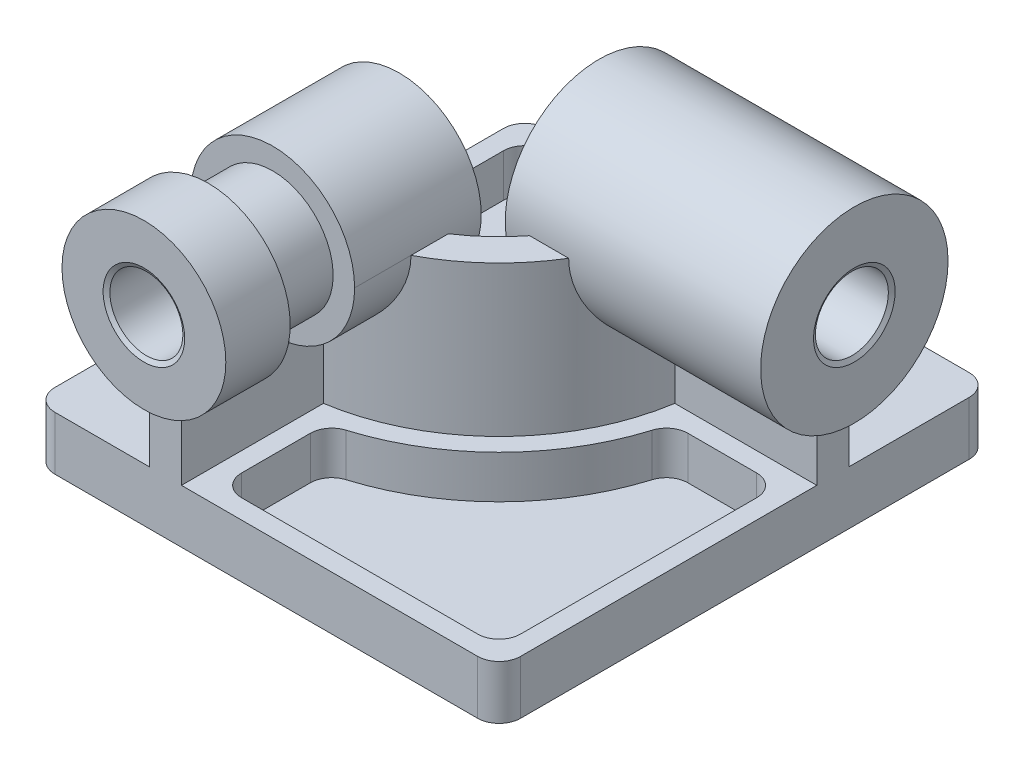
SolidWorks part; units mm, degrees
material "Alloy Steel"
ref_plane "Front Plane" through (0, 0, 0) normal (0, 0, 1) x (1, 0, 0)
ref_plane "Top Plane" through (0, 0, 0) normal (0, 1, 0) x (1, 0, 0)
ref_plane "Right Plane" through (0, 0, 0) normal (1, 0, 0) x (0, 0, -1)
sketch "Sketch1" plane through (0, 0, 0) normal (0, 1, 0) x (1, 0, 0)
  line L0 (0, 0) -> (0, -163) construction
  line L1 (-44, 66) -> (153, 66)
  line L2 (-54, 56) -> (-54, -153)
  line L3 (-44, -163) -> (153, -163)
  line L4 (163, 56) -> (163, -153)
  line L6 (21.1729, -100.3509) -> (22.0551, -100.3509) construction
  line L8 (0, 0) -> (163, 0) construction
  arc A0 (-44, 66) -> (-54, 56) centre (-44, 56) ccw
  arc A1 (-54, -153) -> (-44, -163) centre (-44, -153) ccw
  arc A2 (153, -163) -> (163, -153) centre (153, -153) ccw
  arc A3 (153, 66) -> (163, 56) centre (153, 56) cw
  dimension "D5" = 10
  dimension "D1" = 163
  dimension "D2" = 163
  dimension "D3" = 229
  dimension "D4" = 217
extrude "Boss-Extrude1" add sketch "Sketch1" along normal blind 25
sketch "Sketch2" plane through (0, 25, 0) normal (0, 1, 0) x (1, 0, 0)
  line L0 (0, -83) -> (0, -163)
  line L1 (-44, -163) -> (153, -163) construction
  line L2 (83, 0) -> (163, 0)
  line L3 (163, -153) -> (163, 56) construction
  line L4 (15, -96.8452) -> (15, -163)
  line L5 (96.8452, -15) -> (163, -15)
  line L6 (163, 0) -> (163, -15)
  line L7 (0, -163) -> (15, -163)
  arc A0 (0, -83) -> (83, 0) centre (0, 0) ccw
  arc A1 (15, -96.8452) -> (96.8452, -15) centre (0, 0) ccw
  dimension "D1" = 80
  dimension "D2" = 15
extrude "Boss-Extrude2" add sketch "Sketch2" along normal blind 95 from surface at -25 starting at face at (54.5, 0, 48.5)
sketch "Sketch3" plane through (0, 25, 0) normal (0, 1, 0) x (1, 0, 0)
  line L0 (15, -163) -> (153, -163) construction
  line L1 (118, -103) -> (163, -103)
  line L2 (103, -118) -> (103, -163)
  line L3 (103, -163) -> (153, -163)
  line L4 (163, -103) -> (163, -153)
  line L5 (163, -153) -> (163, -15) construction
  arc A0 (153, -163) -> (163, -153) centre (153, -153) ccw construction
  arc A1 (153, -163) -> (163, -153) centre (153, -153) ccw
  arc A2 (118, -103) -> (103, -118) centre (118, -118) ccw
  dimension "D3" = 15
  dimension "D1" = 60
  dimension "D2" = 60
extrude "Boss-Extrude3" [suppressed] add sketch "Sketch3" along normal blind 10
hole_wizard "CBORE for M8 Hex Head Bolt1" [suppressed] positions "Sketch5" profile "Sketch4" counterbore size "M8" standard "ANSI Metric"
sketch "Sketch5" [suppressed] plane through (0, 35, 0) normal (0, 1, 0) x (1, 0, 0)
  line L0 (105, -165) -> (155, -165) construction
  line L2 (165, -155) -> (165, -105) construction
  point P0 (135, -135)
  dimension "D1" = 30
  dimension "D2" = 30
sketch "Sketch4" plane through (135, 35, 135) normal (1, 0, 0) x (0, 0, 1)
  line L0 (0, 0) -> (0, 35)
  line L1 (0, 35) -> (7.5, 35)
  line L3 (7.5, 35) -> (7.5, 10)
  line L4 (7.5, 10) -> (15, 10)
  line L5 (15, 10) -> (15, 0)
  line L7 (15, 0) -> (0, 0)
  line L11 (0, -6.35) -> (0, 107.95) construction
  dimension "Thru Hole Dia." = 15
  dimension "Thru Hole Depth" = 35
  dimension "C'Bore Dia." = 30
  dimension "C'Bore Depth" = 10
sketch "Sketch6" plane through (0, 25, 0) normal (0, 1, 0) x (1, 0, 0)
  line L10 (154, -24) -> (104.2737, -24)
  line L11 (154, -24) -> (104.2737, -24)
  line L12 (24, -154) -> (153, -154)
  line L13 (24, -104.2737) -> (24, -154)
  line L14 (24, -104.2737) -> (24, -154)
  line L15 (154, -153) -> (154, -24)
  line L18 (20, -154) -> (86, -154)
  line L21 (154, -145) -> (154, -38)
  arc A2 (114.0395, -24) -> (104.4563, -31.1429) centre (114.0395, -34) ccw
  arc A3 (154, -38) -> (149.2411, -29.4835) centre (144, -38) ccw
  arc A4 (153, -154) -> (154, -153) centre (153, -153) ccw
  arc A5 (24, -104.2737) -> (104.2737, -24) centre (0, 0) ccw
  arc A6 (153, -154) -> (154, -153) centre (153, -153) ccw
  arc A7 (24, -104.2737) -> (104.2737, -24) centre (0, 0) ccw
  arc A8 (146.2185, -154.7508) -> (154, -145) centre (144, -145) ccw
  arc A9 (86, -154) -> (95.7508, -146.2185) centre (86, -144) ccw
  arc A10 (20, -154) -> (11.4835, -149.2411) centre (20, -144) cw
  arc A11 (31.1429, -104.4563) -> (24, -114.0395) centre (34, -114.0395) ccw
  dimension "D2" = 10
  dimension "D1" = 9
extrude "Cut-Extrude1" [suppressed] cut sketch "Sketch6" against normal offset from surface (20 mm away) 5
sketch "Sketch7" plane through (0, 0, 163) normal (0, 0, 1) x (1, 0, 0)
  line L0 (0, 95) -> (15, 95) construction
  circle A0 centre (7.5, 95) radius 38.1667
  dimension "D1" = 76.3333
extrude "Boss-Extrude4" add sketch "Sketch7" against normal blind 119 from offset 10
sketch "Sketch8" plane through (163, 0, 0) normal (1, 0, 0) x (0, 0, -1)
  line L0 (-15, 95) -> (0, 95) construction
  circle A0 centre (-7.5, 95) radius 43.6667
  dimension "D1" = 87.3333
extrude "Boss-Extrude5" add sketch "Sketch8" against normal blind 119 from offset 10
sketch "Sketch9" plane through (0, 0, 173) normal (0, 0, 1) x (1, 0, 0)
  circle A0 centre (7.5, 95) radius 17
  dimension "D1" = 34
extrude "Cut-Extrude2" cut sketch "Sketch9" against normal up to next
sketch "Sketch10" plane through (173, 0, 0) normal (1, 0, 0) x (0, 0, -1)
  circle A0 centre (-7.5, 95) radius 17
  dimension "D1" = 34
extrude "Cut-Extrude3" cut sketch "Sketch10" against normal up to next
chamfer "Chamfer1" distance 2 angle 30 4 edges at (54, 95, -9.5) (24.5, 95, 54) (173, 95, -9.5) (24.5, 95, 173)
sketch "Sketch11" plane through (0, 0, 173) normal (0, 0, 1) x (1, 0, 0)
  line L0 (0, 57.5775) -> (0, 67.8502)
  line L2 (15, 67.8502) -> (15, 57.5775)
  arc A0 (15, 67.8502) -> (0, 67.8502) centre (7.5, 95) ccw
  circle A1 centre (7.5, 95) radius 38.1667 construction
  arc A2 (15, 57.5775) -> (0, 57.5775) centre (7.5, 95) ccw
  dimension "D1" = 10
extrude "Cut-Extrude4" cut sketch "Sketch11" against normal blind 30 from offset 30 offset against normal yes
sketch "Sketch12" plane through (0, 25, 0) normal (0, 1, 0) x (1, 0, 0)
  line L8 (24, -104.2737) -> (24, -154)
  line L9 (24, -154) -> (153, -154)
  line L10 (154, -153) -> (154, -24)
  line L11 (24, -111.9509) -> (24, -144)
  line L12 (154, -24) -> (104.2737, -24)
  line L13 (34, -154) -> (144, -154)
  line L14 (154, -144) -> (154, -34)
  line L15 (144, -24) -> (111.9509, -24)
  arc A2 (154, -144) -> (144, -154) centre (144, -144) cw
  arc A3 (34, -154) -> (24, -144) centre (34, -144) cw
  arc A4 (24, -104.2737) -> (104.2737, -24) centre (0, 0) ccw
  arc A5 (153, -154) -> (154, -153) centre (153, -153) ccw
  arc A6 (31.094, -102.3824) -> (102.3824, -31.094) centre (0, 0) ccw
  arc A7 (153, -154) -> (154, -153) centre (153, -153) ccw construction
  arc A8 (31.094, -102.3824) -> (24, -111.9509) centre (34, -111.9509) ccw
  arc A9 (111.9509, -24) -> (102.3824, -31.094) centre (111.9509, -34) ccw
  arc A10 (154, -34) -> (144, -24) centre (144, -34) ccw
  dimension "D2" = 10
  dimension "D3" = 10
  dimension "D1" = 9
extrude "Cut-Extrude5" cut sketch "Sketch12" against normal offset from surface (20 mm away) 5 up to face at (54.5, 0, 48.5)
sketch "Sketch13" plane through (0, 25, 0) normal (0, 1, 0) x (1, 0, 0)
  line L7 (74, 0) -> (74, 47)
  line L8 (0, -74) -> (-35, -74)
  line L13 (154, 9) -> (154, 56)
  line L14 (153, 57) -> (-44, 57)
  line L15 (-45, 56) -> (-45, -153)
  line L16 (-44, -154) -> (-9, -154)
  line L18 (73.4507, 9) -> (154, 9)
  line L19 (-9, -154) -> (-9, -73.4507)
  line L20 (64, 57) -> (-35, 57)
  line L21 (-45, 47) -> (-45, -64)
  arc A4 (-35, -74) -> (-45, -64) centre (-35, -64) cw
  arc A5 (74, 47) -> (64, 57) centre (64, 47) ccw
  arc A6 (-35, 57) -> (-45, 47) centre (-35, 47) ccw
  arc A8 (-9, -73.4507) -> (73.4507, 9) centre (0, 0) ccw
  arc A9 (154, 56) -> (153, 57) centre (153, 56) ccw
  arc A10 (-44, 57) -> (-45, 56) centre (-44, 56) ccw
  arc A11 (-45, -153) -> (-44, -154) centre (-44, -153) ccw
  arc A12 (0, -74) -> (74, 0) centre (0, 0) ccw
  arc A14 (-44, 57) -> (-45, 56) centre (-44, 56) ccw construction
  dimension "D2" = 10
  dimension "D3" = 10
  dimension "D1" = 9
extrude "Cut-Extrude7" cut sketch "Sketch13" against normal up to surface (20 mm away) up to face at (93.1669, 5, 93.1669)
equation "\"A\"= 229"
equation "\"D1@Sketch1\"=\"C\""
equation "\"D2@Sketch1\"=\"C\""
equation "\"B\"= 217"
equation "\"D3@Sketch1\"=\"A\""
equation "\"C\"= 163"
equation "\"D4@Sketch1\"=\"B\""
equation "\"D1@Sketch7\"=\"X\""
equation "\"D\"= 119"
equation "\"D1@Boss-Extrude4\"=\"D\""
equation "\"D1@Sketch8\"=\"Y\""
equation "\"D1@Boss-Extrude5\"=\"D\""
equation "\"E\"= 34"
equation "\"D1@Sketch9\"=\"E\""
equation "\"D1@Sketch10\"=\"E\""
equation "\"X\"= \"A\" / 3"
equation "\"Y\"= \"B\" / 3 + 15"
